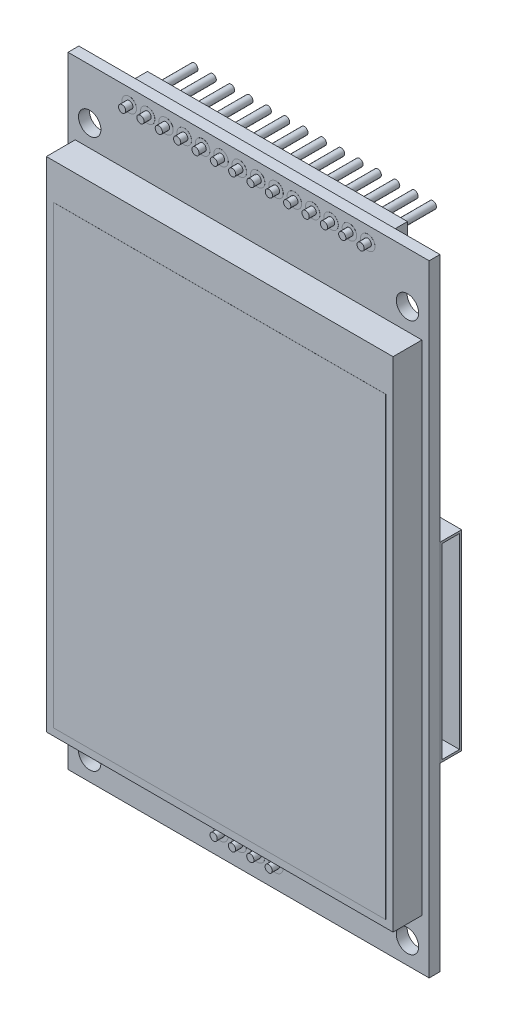
SolidWorks part; units mm, degrees
ref_plane "Front Plane" through (0, 0, 0) normal (0, 0, 1) x (1, 0, 0)
ref_plane "Top Plane" through (0, 0, 0) normal (0, 1, 0) x (1, 0, 0)
ref_plane "Right Plane" through (0, 0, 0) normal (1, 0, 0) x (0, 0, -1)
sketch "Sketch1" plane through (0, 0, 0) normal (0, 0, 1) x (1, 0, 0)
  line L1 (0, 0) -> (50, 0)
  line L2 (0, 0) -> (0, 86)
  line L3 (0, 86) -> (50, 86)
  line L4 (50, 0) -> (50, 86)
  dimension "D1" = 50
  dimension "D2" = 86
extrude "Boss-Extrude1" add sketch "Sketch1" along normal blind 1.5
sketch "Sketch2" plane through (0, 0, 1.5) normal (0, 0, 1) x (1, 0, 0)
  line L0 (3, 86) -> (3, 0) construction
  line L1 (50, 86) -> (0, 86) construction
  line L2 (0, 0) -> (50, 0) construction
  line L3 (47, 86) -> (47, 0) construction
  line L4 (0, 79) -> (50, 79) construction
  line L5 (0, 86) -> (0, 0) construction
  line L6 (50, 0) -> (50, 86) construction
  line L7 (0, 3) -> (50, 3) construction
  circle A0 centre (3, 79) radius 1.55
  circle A1 centre (47, 79) radius 1.55
  circle A2 centre (47, 3) radius 1.55
  circle A3 centre (3, 3) radius 1.55
  dimension "D5" = 3.1
  dimension "D6" = 3.1
  dimension "D7" = 3.1
  dimension "D8" = 3.1
  dimension "D1" = 3
  dimension "D2" = 3
  dimension "D3" = 7
  dimension "D4" = 3
extrude "Cut-Extrude1" cut sketch "Sketch2" against normal blind 1.5
sketch "Sketch3" plane through (0, 0, 1.5) normal (0, 0, 1) x (1, 0, 0)
  line L0 (0, 86) -> (0, 0) construction
  line L1 (1, 76) -> (49, 76)
  line L2 (1, 76) -> (1, 7)
  line L3 (1, 7) -> (49, 7)
  line L4 (49, 76) -> (49, 7)
  line L5 (50, 0) -> (50, 86) construction
  line L6 (50, 86) -> (0, 86) construction
  line L7 (0, 0) -> (50, 0) construction
  dimension "D1" = 1
  dimension "D2" = 1
  dimension "D3" = 10
  dimension "D4" = 7
extrude "Boss-Extrude2" add sketch "Sketch3" along normal blind 4
sketch "Sketch4" plane through (0, 0, 5.5) normal (0, 0, 1) x (1, 0, 0)
  line L0 (1, 76) -> (1, 7) construction
  line L1 (2, 71) -> (48, 71)
  line L2 (2, 71) -> (2, 8)
  line L3 (2, 8) -> (48, 8)
  line L4 (48, 71) -> (48, 8)
  line L5 (49, 7) -> (49, 76) construction
  line L6 (49, 76) -> (1, 76) construction
  line L7 (1, 7) -> (49, 7) construction
  dimension "D1" = 1
  dimension "D2" = 1
  dimension "D3" = 5
  dimension "D4" = 1
extrude "Boss-Extrude3" add sketch "Sketch4" along normal blind 0.01
sketch "Sketch5" plane through (0, 0, 1.5) normal (0, 0, 1) x (1, 0, 0)
  line L0 (0, 83.96) -> (50, 83.96) construction
  line L1 (0, 86) -> (0, 0) construction
  line L2 (50, 0) -> (50, 86) construction
  line L3 (8.49, 86) -> (8.49, 83.96) construction
  line L4 (50, 86) -> (0, 86) construction
  line L5 (-0.0031, 3) -> (49.9893, 3) construction
  line L6 (21.16, 6.584) -> (21.16, 0.084) construction
  line L7 (0, 0) -> (50, 0) construction
  circle A0 centre (8.49, 83.96) radius 1
  circle A1 centre (11.03, 83.96) radius 1
  circle A2 centre (13.57, 83.96) radius 1
  circle A3 centre (16.11, 83.96) radius 1
  circle A4 centre (18.65, 83.96) radius 1
  circle A5 centre (21.19, 83.96) radius 1
  circle A6 centre (23.73, 83.96) radius 1
  circle A7 centre (26.27, 83.96) radius 1
  circle A8 centre (28.81, 83.96) radius 1
  circle A9 centre (31.35, 83.96) radius 1
  circle A10 centre (33.89, 83.96) radius 1
  circle A11 centre (36.43, 83.96) radius 1
  circle A12 centre (38.97, 83.96) radius 1
  circle A13 centre (41.51, 83.96) radius 1
  circle A14 centre (21.1602, 3.0003) radius 1
  circle A15 centre (23.7002, 3.0003) radius 1
  circle A16 centre (26.2402, 3.0003) radius 1
  circle A17 centre (28.7802, 3.0003) radius 1
  dimension "D3" = 2
  dimension "D5" = 21.16
  dimension "D7" = 2
  dimension "D1" = 2.04
  dimension "D2" = 8.49
  dimension "D6" = 3
  dimension "D8" = 11.03
  dimension "D9" = 21.1602
  dimension "D10" = 3.0003
  dimension "D4" = 14
  dimension "D11" = 4
extrude "Boss-Extrude4" add sketch "Sketch5" along normal blind 0.01
sketch "Sketch6" plane through (0, 0, 1.5) normal (0, 0, 1) x (1, 0, 0)
  circle A0 centre (8.49, 83.96) radius 0.5
  circle A1 centre (11.03, 83.96) radius 0.5
  circle A2 centre (13.57, 83.96) radius 0.5
  circle A3 centre (16.11, 83.96) radius 0.5
  circle A4 centre (18.65, 83.96) radius 0.5
  circle A5 centre (21.19, 83.96) radius 0.5
  circle A6 centre (23.73, 83.96) radius 0.5
  circle A7 centre (26.27, 83.96) radius 0.5
  circle A8 centre (28.81, 83.96) radius 0.5
  circle A9 centre (31.35, 83.96) radius 0.5
  circle A10 centre (33.89, 83.96) radius 0.5
  circle A11 centre (36.43, 83.96) radius 0.5
  circle A12 centre (38.97, 83.96) radius 0.5
  circle A13 centre (41.51, 83.96) radius 0.5
  circle A14 centre (21.1602, 3.0003) radius 0.5
  circle A15 centre (21.1602, 3.0003) radius 1 construction
  circle A16 centre (23.7002, 3.0003) radius 0.5
  circle A17 centre (26.2402, 3.0003) radius 0.5
  circle A18 centre (28.7802, 3.0003) radius 0.5
  dimension "D1" = 1
  dimension "D3" = 1
  dimension "D2" = 14
  dimension "D4" = 4
extrude "Boss-Extrude5" add sketch "Sketch6" along normal blind 1 and the other way blind 9
sketch "Sketch8" plane through (0, 0, 0) normal (0, 0, -1) x (-1, 0, 0)
  line L0 (0, 86) -> (0, 0) construction
  line L1 (-43, 85.2) -> (-7, 85.2)
  line L2 (-43, 85.2) -> (-43, 82.7)
  line L3 (-43, 82.7) -> (-7, 82.7)
  line L4 (-7, 85.2) -> (-7, 82.7)
  line L5 (-50, 0) -> (-50, 86) construction
  line L6 (-50, 86) -> (0, 86) construction
  line L7 (0, 0) -> (-50, 0) construction
  line L8 (-30.5, 4.3) -> (-19.5, 4.3)
  line L9 (-30.5, 4.3) -> (-30.5, 1.8)
  line L10 (-30.5, 1.8) -> (-19.5, 1.8)
  line L11 (-19.5, 4.3) -> (-19.5, 1.8)
  dimension "D1" = 7
  dimension "D2" = 7
  dimension "D3" = 0.8
  dimension "D4" = 2.5
  dimension "D5" = 19.5
  dimension "D6" = 19.5
  dimension "D7" = 1.8
  dimension "D8" = 2.5
extrude "Boss-Extrude6" add sketch "Sketch8" along normal blind 2.5
sketch "Sketch9" plane through (0, 0, 0) normal (0, 0, -1) x (-1, 0, 0)
  line L0 (-50, 51.5) -> (-38.5, 51.5)
  line L1 (-38.5, 51.5) -> (-38.5, 27)
  line L2 (-38.5, 27) -> (-43.5, 27)
  line L3 (-43.5, 27) -> (-45.7361, 25)
  line L4 (-45.7361, 25) -> (-50, 25)
  line L5 (-50, 25) -> (-50, 111)
  line L6 (-50, 0) -> (-50, 86) construction
  line L7 (0, 0) -> (-50, 0) construction
  point P11 (-41, 27)
  line M17 (-50, 86) -> (-50, 0)
  dimension "D1" = 24.5
  dimension "D2" = 5
  dimension "D3" = 11.5
  dimension "D4" = 0
  dimension "D5" = 0
  dimension "D6" = 25
  dimension "D7" = 2
  dimension "D8" = 3
extrude "Boss-Extrude7" add sketch "Sketch9" along normal blind 3 separate body contours L4 L3 L2 L1 L0 M17
sketch "Sketch10" plane through (50, 0, 0) normal (1, 0, 0) x (0, 0, -1)
  line L0 (3, 51.5) -> (3, 25) construction
  line L1 (2.7, 51.2) -> (0.3, 51.2)
  line L2 (2.7, 51.2) -> (2.7, 25.3)
  line L3 (2.7, 25.3) -> (0.3, 25.3)
  line L4 (0.3, 51.2) -> (0.3, 25.3)
  line L5 (0, 51.5) -> (0, 25) construction
  line L6 (3, 51.5) -> (0, 51.5) construction
  line L7 (3, 25) -> (0, 25) construction
  point P10 (1.5, 51.5)
  dimension "D1" = 0.3
  dimension "D2" = 0.3
  dimension "D3" = 0.3
  dimension "D4" = 0.3
extrude "Cut-Extrude2" cut sketch "Sketch10" against normal blind 4
